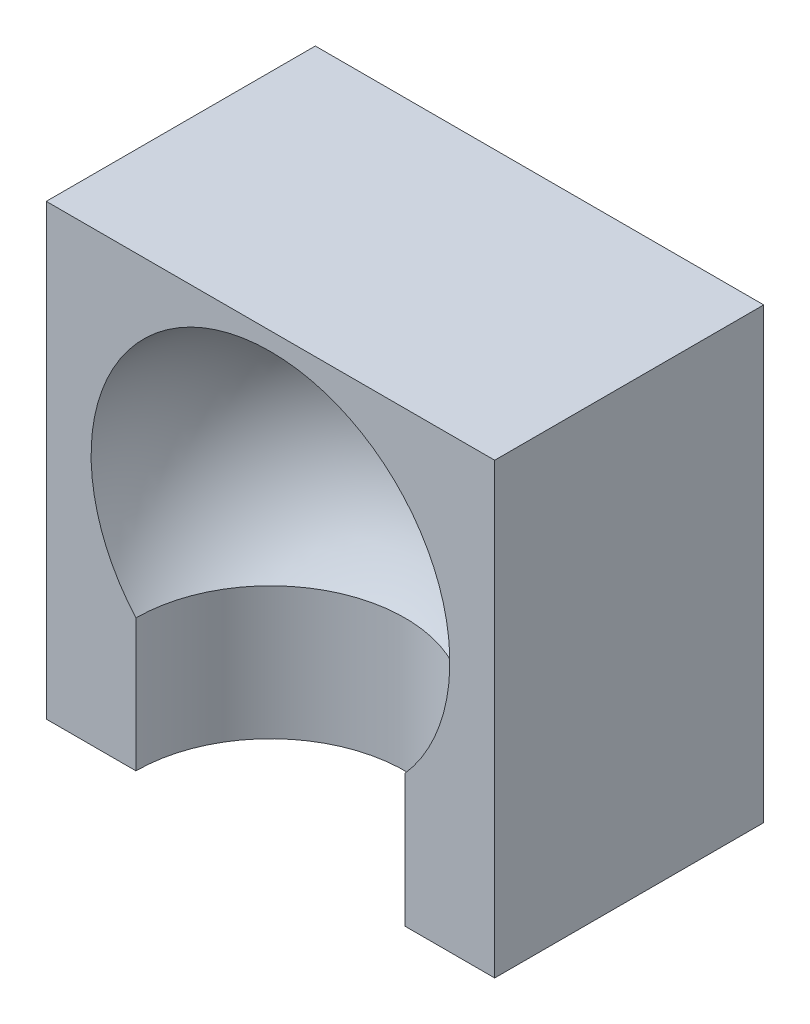
SolidWorks part; units mm, degrees
ref_plane "Front Plane" through (0, 0, 0) normal (0, 0, 1) x (1, 0, 0)
ref_plane "Top Plane" through (0, 0, 0) normal (0, 1, 0) x (1, 0, 0)
ref_plane "Right Plane" through (0, 0, 0) normal (1, 0, 0) x (0, 0, -1)
sketch "Sketch1" plane through (0, 0, 0) normal (0, 0, 1) x (1, 0, 0)
  line L1 (0, 0) -> (25, 0)
  line L2 (0, 0) -> (0, 25)
  line L3 (0, 25) -> (25, 25)
  line L4 (25, 0) -> (25, 25)
  dimension "D1" = 25
  dimension "D2" = 25
extrude "Boss-Extrude1" add sketch "Sketch1" along normal blind 15
sketch "Sketch2" plane through (0, 0, 15) normal (0, 0, 1) x (1, 0, 0)
  line L0 (12.5, 25) -> (12.5, 0) construction
  line L1 (25, 25) -> (0, 25) construction
  line L2 (0, 0) -> (25, 0) construction
  line L3 (12.5, 24) -> (12.5, 4)
  arc A0 (12.5, 4) -> (12.5, 24) centre (12.5, 14) ccw
  point P7 (12.5, 12.5)
  point P10 (0, 0)
  point P11 (0, 0)
  point P12 (12.5, 14)
  dimension "D1" = 10
  dimension "D2" = 11
revolve "Cut-Revolve2" cut sketch "Sketch2" angle 360 about L3
sketch "Sketch3" plane through (0, 0, 0) normal (0, -1, 0) x (1, 0, 0)
  line L0 (0, 15) -> (25, 15) construction
  circle A0 centre (12.5, 15) radius 7.5
  dimension "D1" = 15
extrude "Cut-Extrude1" cut sketch "Sketch3" against normal blind 15
